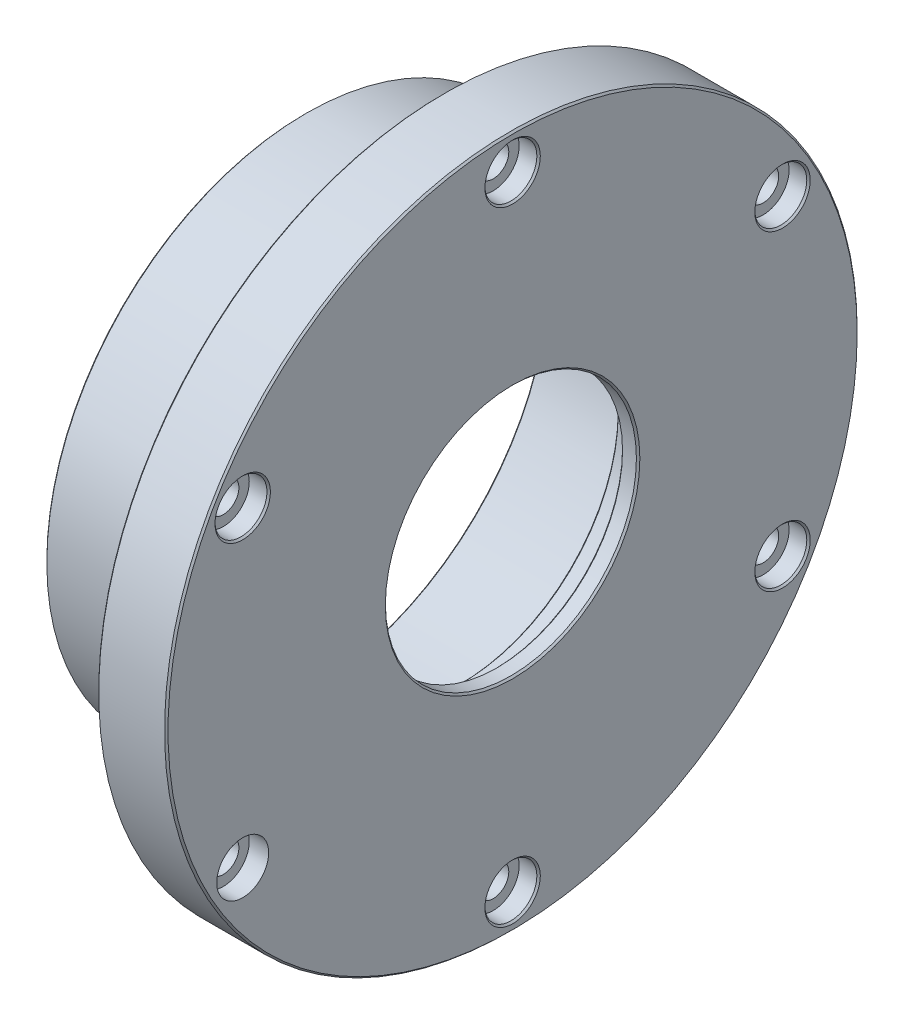
SolidWorks part; units mm, degrees
ref_plane "Front Plane" through (0, 0, 0) normal (0, 0, 1) x (1, 0, 0)
ref_plane "Top Plane" through (0, 0, 0) normal (0, 1, 0) x (1, 0, 0)
ref_plane "Right Plane" through (0, 0, 0) normal (1, 0, 0) x (0, 0, -1)
sketch "Sketch1" plane through (0, 0, 0) normal (0, 0, 1) x (1, 0, 0)
  line L0 (-15.2619, -33.1832) -> (53.5176, -33.1832)
  line L1 (22.9387, 66.8168) -> (42.9387, 66.8168)
  line L2 (-17.0613, 41.8168) -> (-17.0613, 36.8168)
  line L3 (37.9387, 3.0668) -> (42.9387, 3.0668)
  line L5 (42.9387, 66.8168) -> (42.9387, 3.0668)
  line L16 (-17.0613, 41.8168) -> (22.9387, 41.8168)
  line L17 (22.9387, 66.8168) -> (22.9387, 41.8168)
  line L20 (-17.0613, 36.8168) -> (21.9387, 36.8168)
  line L21 (21.9387, 26.8168) -> (21.9387, 36.8168)
  line L22 (21.9387, 26.8168) -> (27.9387, 26.8168)
  line L25 (37.9387, 11.8168) -> (37.9387, 3.0668)
  line L32 (37.9387, 11.8168) -> (27.9387, 11.8168)
  line L33 (27.9387, 26.8168) -> (27.9387, 11.8168)
  dimension "D1" = 63.75
  dimension "D2" = 40
  dimension "D3" = 36.25
  dimension "D4" = 39
  dimension "D5" = 10
  dimension "D6" = 5
  dimension "D7" = 20
  dimension "D8" = 5
  dimension "D9" = 15
  dimension "D11" = 10
revolve "Revolve1" add sketch "Sketch1" angle 360 about L0
sketch "Sketch2" plane through (42.9387, 0, 0) normal (1, 0, 0) x (0, 0, -1)
  line L0 (0, -33.1832) -> (0, 56.8168)
  line L1 (0, -33.1832) -> (77.9423, 11.8168)
  line L2 (0, -33.1832) -> (77.9423, -78.1832)
  line L3 (0, -33.1832) -> (0, -123.1832)
  line L4 (0, -33.1832) -> (-77.9423, -78.1832)
  line L5 (0, -33.1832) -> (-77.9423, 11.8168)
  point P6 (0, 56.8168)
  point P9 (0, -33.1832)
  point P24 (-77.9423, 11.8168)
  point P27 (-77.9423, -78.1832)
  point P30 (0, -123.1832)
  point P33 (77.9423, -78.1832)
  point P36 (77.9423, 11.8168)
  dimension "D1" = 90
  dimension "D2" = 6
hole_wizard "CBORE for M8 Hex Socket Thin Head Cap Screw1" positions "Sketch2" profile "Sketch3" counterbore size "M8" standard "DIN"
sketch "Sketch3" plane through (42.9387, 11.8168, -77.9423) normal (0, 1, 0) x (0, 0, -1)
  line L0 (0, 0) -> (0, 22.7039)
  line L1 (0, 22.7039) -> (4.5, 20)
  line L2 (4.5, 20) -> (4.5, 5.6)
  line L3 (4.5, 5.6) -> (7.5, 5.6)
  line L4 (7.5, 5.6) -> (7.5, 0)
  line L5 (7.5, 0) -> (0, 0)
  line L10 (0, 22.7039) -> (-4.5, 20) construction
  line L11 (0, -6.35) -> (0, 107.95) construction
  dimension "Hole Dia." = 9
  dimension "Hole Depth" = 20
  dimension "C'Bore Dia." = 15
  dimension "C'Bore Depth" = 5.6
  dimension "Drill Angle" = 118
chamfer "Chamfer1" distance 0.5 angle 45 19 edges at (22.9387, -33.1832, 100) (-17.0613, -33.1832, 75) (22.9387, -123.1832, -4.5) (22.9387, -78.1832, -82.4423) (22.9387, 11.8168, -82.4423) (22.9387, 56.8168, -4.5) (22.9387, 11.8168, 73.4423) (22.9387, -78.1832, 73.4423) (42.9387, -123.1832, -7.5) (42.9387, -78.1832, -85.4423) (42.9387, 11.8168, -85.4423) (42.9387, 56.8168, -7.5) (42.9387, 11.8168, 70.4423) (-17.0613, -33.1832, 70) (42.9387, -33.1832, 36.25) (42.9387, -33.1832, 100) (37.9387, -33.1832, 36.25) (27.9387, -33.1832, 45) (21.9387, -33.1832, 60)
